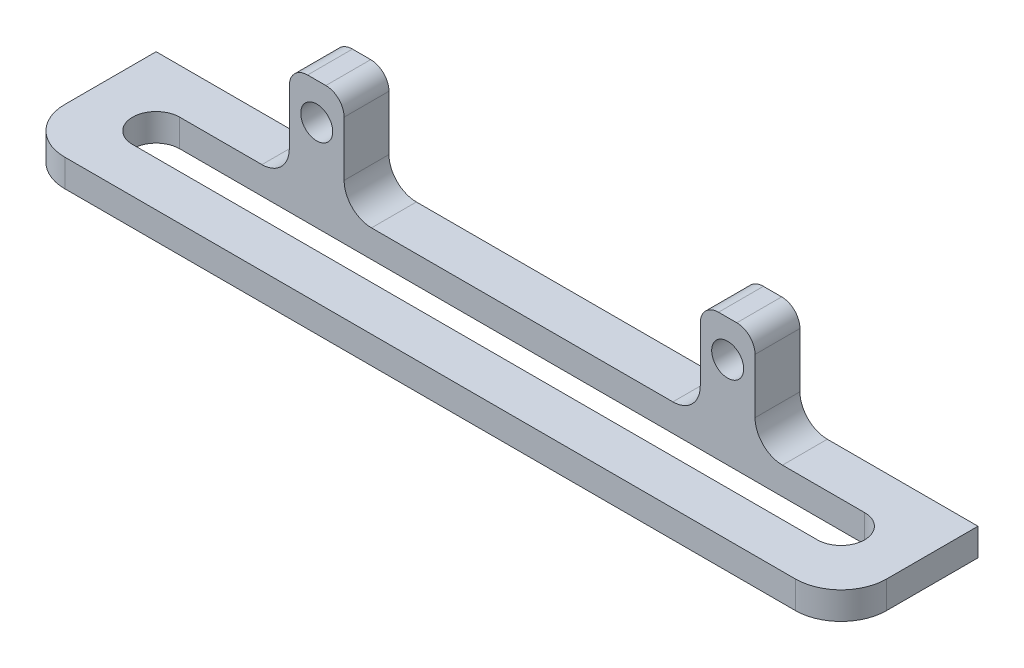
SolidWorks part; units mm, degrees
ref_plane "Front Plane" through (0, 0, 0) normal (0, 0, 1) x (1, 0, 0)
ref_plane "Top Plane" through (0, 0, 0) normal (0, 1, 0) x (1, 0, 0)
ref_plane "Right Plane" through (0, 0, 0) normal (1, 0, 0) x (0, 0, -1)
sketch "Sketch1" plane through (0, 0, 0) normal (0, 1, 0) x (1, 0, 0)
  line L0 (-37.5, 0) -> (37.5, 0) construction
  line L1 (-45, 7.5) -> (45, 7.5)
  line L2 (-45, 7.5) -> (-45, -7.5)
  line L3 (-45, -7.5) -> (45, -7.5)
  line L4 (45, 7.5) -> (45, -7.5)
  line L5 (-45, 7.5) -> (45, -7.5) construction
  line L6 (-45, -7.5) -> (45, 7.5) construction
  line L7 (-37.5, 2.5863) -> (37.5, 2.5863)
  line L8 (-37.5, -2.5863) -> (37.5, -2.5863)
  arc A0 (-37.5, 2.5863) -> (-37.5, -2.5863) centre (-37.5, 0) ccw
  arc A1 (37.5, -2.5863) -> (37.5, 2.5863) centre (37.5, 0) ccw
  point P0 (0, 0)
  point P8 (0, 0)
  dimension "D1" = 90
  dimension "D2" = 15
  dimension "D3" = 7.5
  dimension "D4" = 7.5
extrude "Boss-Extrude1" add sketch "Sketch1" along normal blind 3
fillet "Fillet1" radius 5 2 edges at (45, 1.5, 7.5) (-45, 1.5, 7.5)
sketch "Sketch2" plane through (0, 3, 0) normal (0, 1, 0) x (1, 0, 0)
  line L0 (45, 7.5) -> (-45, 7.5) construction
  line L1 (-25.5, 7.5) -> (-19.5, 7.5)
  line L2 (-25.5, 7.5) -> (-25.5, 2.5863)
  line L3 (-25.5, 2.5863) -> (-19.5, 2.5863)
  line L4 (-19.5, 7.5) -> (-19.5, 2.5863)
  line L5 (37.5, 2.5863) -> (-37.5, 2.5863) construction
  line L6 (19.5, 7.5) -> (25.5, 7.5)
  line L7 (19.5, 7.5) -> (19.5, 2.5863)
  line L8 (19.5, 2.5863) -> (25.5, 2.5863)
  line L9 (25.5, 7.5) -> (25.5, 2.5863)
  point P10 (-22.5, 2.5863)
  point P11 (0, 7.5)
  point P12 (22.5, 2.5863)
  point P15 (0, 0)
  dimension "D1" = 6
  dimension "D2" = 6
  dimension "D3" = 22.5
  dimension "D4" = 22.5
  dimension "D5" = 0
  dimension "D6" = 0
extrude "Boss-Extrude2" add sketch "Sketch2" along normal blind 11
sketch "Sketch3" plane through (0, 0, -2.5863) normal (0, 0, 1) x (1, 0, 0)
  line L1 (-40, 0) -> (40, 0) construction
  circle A0 centre (-22.5, 10) radius 1.75
  point P4 (0, 0)
  point P5 (0, 0)
  dimension "D1" = 3.5
  dimension "D2" = 10
extrude "Cut-Extrude1" cut sketch "Sketch3" against normal up to surface (4.9137 mm away) contours A0 up to face at (0, 6.1667, -7.5)
mirror "Mirror1" about plane through (0, 0, 0) normal (1, 0, 0) of "Cut-Extrude1"
fillet "Fillet2" radius 2 4 edges at (25.5, 14, -5.0431) (19.5, 14, -5.0431) (-19.5, 14, -5.0431) (-25.5, 14, -5.0431)
fillet "Fillet3" radius 3 4 edges at (25.5, 3, -5.0431) (19.5, 3, -5.0431) (-19.5, 3, -5.0431) (-25.5, 3, -5.0431)
